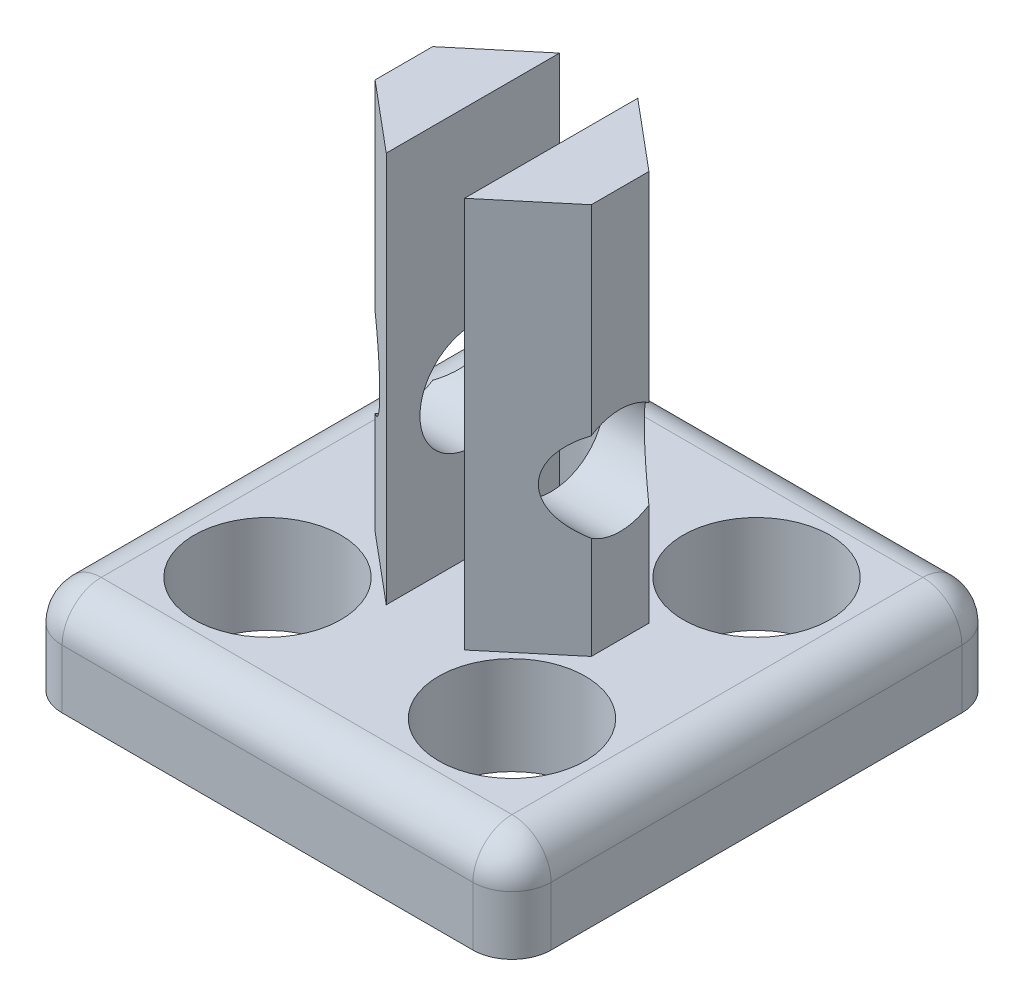
SolidWorks part; units mm, degrees
ref_plane "Front Plane" through (0, 0, 0) normal (0, 0, 1) x (1, 0, 0)
ref_plane "Top Plane" through (0, 0, 0) normal (0, 1, 0) x (1, 0, 0)
ref_plane "Right Plane" through (0, 0, 0) normal (1, 0, 0) x (0, 0, -1)
sketch "Sketch1" plane through (0, 0, 0) normal (0, 1, 0) x (1, 0, 0)
  line L0 (0, 12.208) -> (0, -19.1109) construction
  line L1 (-6.35, -6.35) -> (6.35, -6.35)
  line L2 (-6.35, -6.35) -> (-6.35, 6.35)
  line L3 (-6.35, 6.35) -> (6.35, 6.35)
  line L4 (6.35, -6.35) -> (6.35, 6.35)
  line L5 (-6.35, -6.35) -> (6.35, 6.35) construction
  line L6 (-6.35, 6.35) -> (6.35, -6.35) construction
  line L7 (-21.3979, 0) -> (34.337, 0) construction
  circle A0 centre (-3.175, 3.175) radius 1.905
  circle A1 centre (3.175, 3.175) radius 1.905
  circle A2 centre (3.175, -3.175) radius 1.905
  circle A3 centre (-3.175, -3.175) radius 1.905
  point P0 (0, 0)
  point P18 (0, 0)
  point P19 (0, 0)
  dimension "D3" = 3.81
  dimension "D1" = 12.7
  dimension "D2" = 12.7
  dimension "D4" = 3.175
extrude "Boss-Extrude1" add sketch "Sketch1" along normal blind 2.54
sketch "Sketch2" plane through (0, 2.54, 0) normal (0, 1, 0) x (1, 0, 0)
  line L0 (0, 0) -> (-7.7131, 0) construction
  line L5 (-1.016, 5.1275) -> (1.016, 5.1275)
  line L6 (2.8079, -0.748) -> (2.8079, 0.748)
  line L8 (-1.016, -5.1275) -> (1.016, -5.1275)
  line L9 (-1.016, -5.1275) -> (-1.016, 5.1275)
  line L11 (1.016, -5.1275) -> (1.016, 5.1275)
  line L12 (-1.016, -5.1275) -> (1.016, 5.1275) construction
  line L13 (-1.016, 5.1275) -> (1.016, -5.1275) construction
  line L14 (0, 0) -> (0, 7.6198) construction
  line L15 (-2.8079, 0.748) -> (-2.8079, -0.748)
  line L20 (-2.8079, 0.748) -> (-1.016, 2.2498)
  line L21 (-4.424, -0.748) -> (4.424, -0.748)
  line L22 (-4.424, -0.748) -> (-4.424, 0.748)
  line L23 (-4.424, 0.748) -> (4.424, 0.748)
  line L24 (4.424, -0.748) -> (4.424, 0.748)
  line L25 (-4.424, -0.748) -> (4.424, 0.748) construction
  line L26 (-4.424, 0.748) -> (4.424, -0.748) construction
  line L27 (2.8079, 0.748) -> (1.016, 2.2498)
  line L28 (2.8079, -0.748) -> (1.016, -2.2498)
  line L29 (-2.8079, -0.748) -> (-1.016, -2.2498)
  point P0 (0, 0)
  point P1 (0, 0)
  point P3 (0, 0)
  point P6 (-1.16, 2.2498)
  point P7 (0, 0)
  point P8 (0, 0)
  dimension "D1" = 2.032
  dimension "D2" = 0
extrude "Boss-Extrude2" add sketch "Sketch2" along normal blind 10.16 contours L20 L23 L9 | L23 L15 L21 L9 | L21 L29 L9 | L23 L27 L11 | L23 L11 L21 L6 | L28 L21 L11
sketch "Sketch3" plane through (2.8079, 0, 0) normal (1, 0, 0) x (0, 0, -1)
  line L0 (-0.748, 2.54) -> (0.748, 2.54) construction
  circle A0 centre (0, 6.35) radius 1.375
  dimension "D1" = 2.75
  dimension "D2" = 3.81
extrude "Cut-Extrude1" cut sketch "Sketch3" against normal through all
fillet "Fillet1" radius 1.016 8 edges at (6.35, 1.27, -6.35) (0, 2.54, -6.35) (-6.35, 1.27, -6.35) (-6.35, 1.27, 6.35) (-6.35, 2.54, 0) (6.35, 1.27, 6.35) (6.35, 2.54, 0) (0, 2.54, 6.35)
